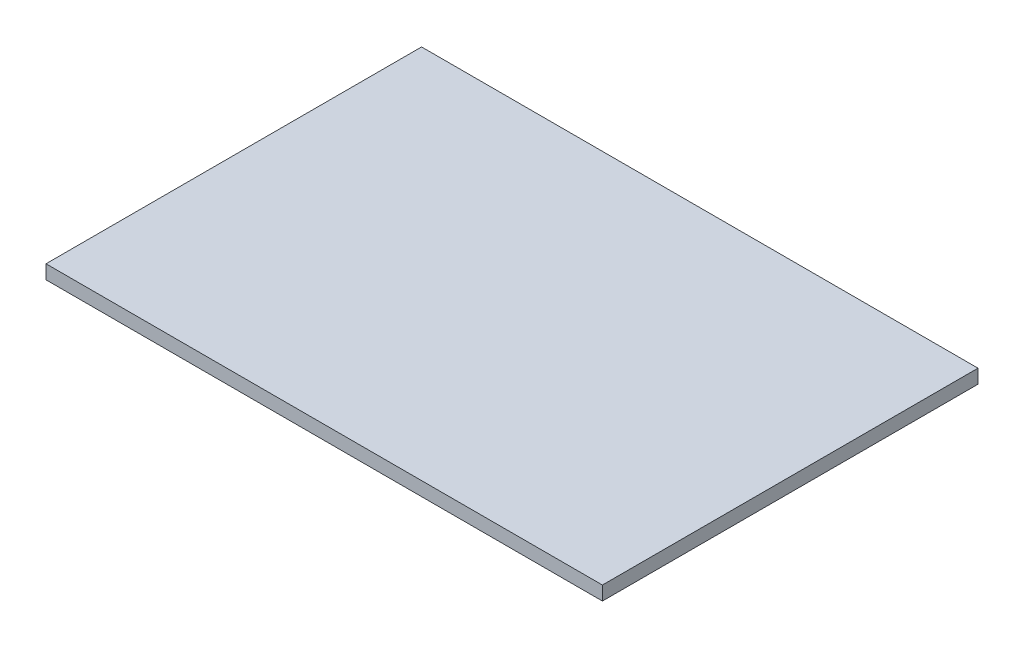
SolidWorks part; units mm, degrees
ref_plane "Front Plane" through (0, 0, 0) normal (0, 0, 1) x (1, 0, 0)
ref_plane "Top Plane" through (0, 0, 0) normal (0, 1, 0) x (1, 0, 0)
ref_plane "Right Plane" through (0, 0, 0) normal (1, 0, 0) x (0, 0, -1)
sketch "Sketch1" plane through (0, 0, 0) normal (0, 1, 0) x (1, 0, 0)
  line L1 (0, 0) -> (40, 0)
  line L2 (0, 0) -> (0, -27)
  line L3 (0, -27) -> (40, -27)
  line L4 (40, 0) -> (40, -27)
  dimension "D1" = 27
  dimension "D2" = 40
extrude "Boss-Extrude1" add sketch "Sketch1" along normal blind 1
